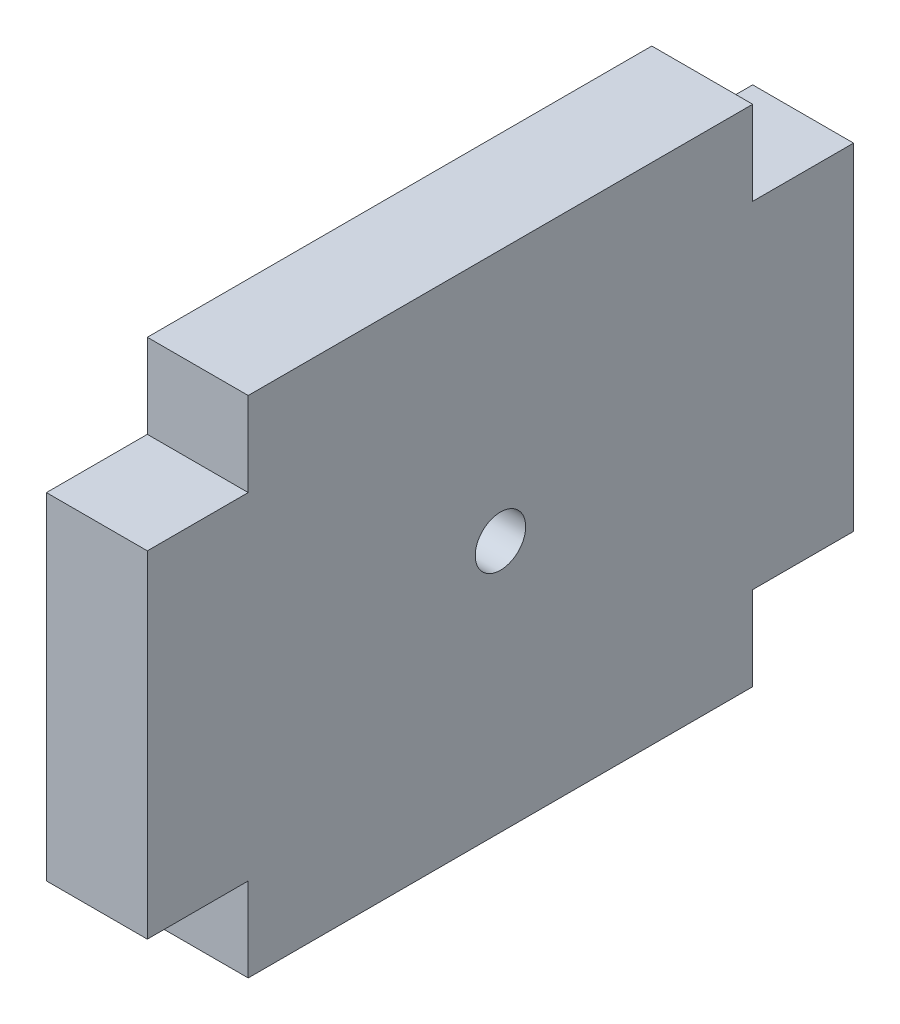
SolidWorks part; units mm, degrees
ref_plane "Přední rovina" through (0, 0, 0) normal (0, 0, 1) x (1, 0, 0)
ref_plane "Horní rovina" through (0, 0, 0) normal (0, 1, 0) x (1, 0, 0)
ref_plane "Pravá rovina" through (0, 0, 0) normal (1, 0, 0) x (0, 0, -1)
sketch "Skica1" plane through (0, 0, 0) normal (1, 0, 0) x (0, 0, -1)
  line L0 (-32.3027, 0) -> (29.782, 0) construction
  line L1 (-7.5, -7.5) -> (7.5, -7.5)
  line L2 (-7.5, -7.5) -> (-7.5, 7.5)
  line L3 (-7.5, 7.5) -> (7.5, 7.5)
  line L4 (7.5, -7.5) -> (7.5, 7.5)
  line L5 (-7.5, -7.5) -> (7.5, 7.5) construction
  line L6 (-7.5, 7.5) -> (7.5, -7.5) construction
  line L7 (0, 19.1987) -> (0, -27.6616) construction
  line L8 (-7.5, 5) -> (-10.5, -5) construction
  line L9 (7.5, -5) -> (10.5, -5)
  line L10 (7.5, -5) -> (7.5, 5)
  line L11 (7.5, 5) -> (10.5, 5)
  line L12 (10.5, -5) -> (10.5, 5)
  line L13 (7.5, -5) -> (10.5, 5) construction
  line L14 (7.5, 5) -> (10.5, -5) construction
  line L15 (-7.5, -5) -> (-10.5, 5) construction
  line L16 (-7.5, 5) -> (-10.5, 5)
  line L17 (-10.5, -5) -> (-10.5, 5)
  line L18 (-7.5, -5) -> (-10.5, -5)
  line L19 (-7.5, -5) -> (-7.5, 5)
  point P0 (0, 0)
  point P10 (9, 0)
  point P15 (-9, 0)
  dimension "D1" = 15
  dimension "D2" = 15
  dimension "D3" = 10
  dimension "D4" = 3
extrude "Přidat vysunutím1" add sketch "Skica1" along normal blind 3 contours L9 L12 L11 L4 | L1 L4 L3 L2 | L18 L2 L16 L17
sketch "Skica2" plane through (3, 0, 0) normal (1, 0, 0) x (0, 0, -1)
  circle A0 centre (0, 0) radius 0.75
  dimension "D1" = 1.5
extrude "Odebrat vysunutím1" cut sketch "Skica2" against normal blind 3
